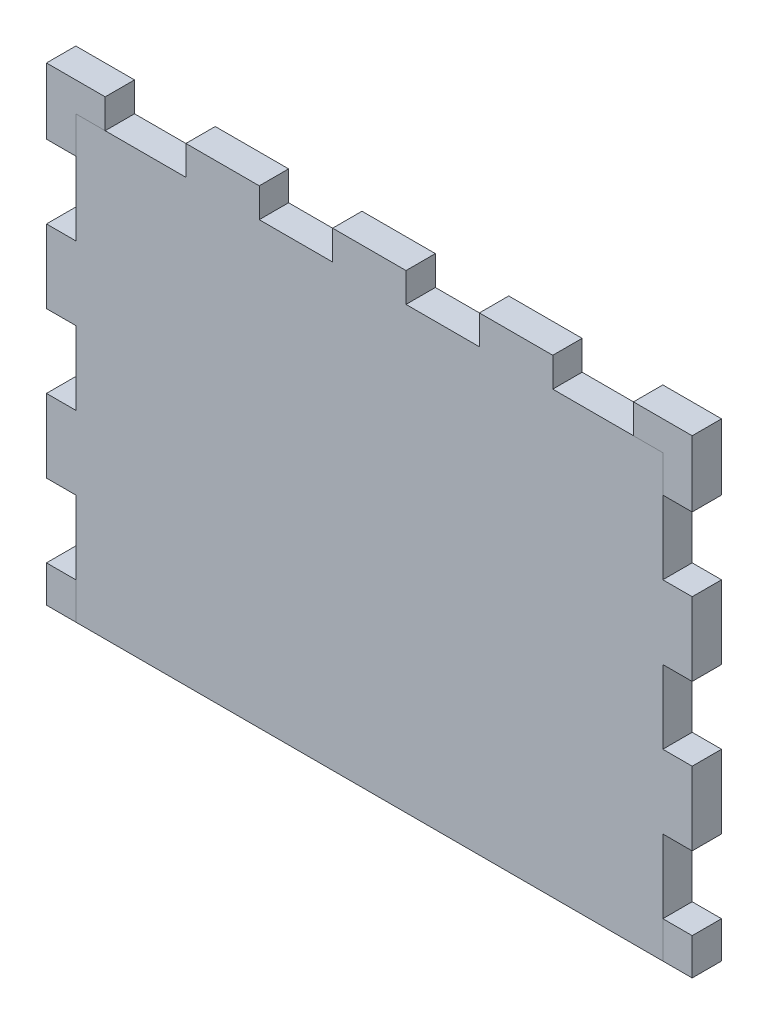
SolidWorks part; units mm, degrees
ref_plane "Front Plane" through (0, 0, 0) normal (0, 0, 1) x (1, 0, 0)
ref_plane "Top Plane" through (0, 0, 0) normal (0, 1, 0) x (1, 0, 0)
ref_plane "Right Plane" through (0, 0, 0) normal (1, 0, 0) x (0, 0, -1)
sketch "Sketch1" plane through (0, 0, 0) normal (0, 0, 1) x (1, 0, 0)
  line L0 (-40, 30) -> (-20, 30)
  line L1 (-40, -30) -> (40, -30)
  line L2 (-40, -30) -> (-40, 30)
  line L3 (-40, 30) -> (40, 30)
  line L4 (40, -30) -> (40, 30)
  line L5 (0, 30) -> (0, -30) construction
  line L6 (-40, 0) -> (40, 0) construction
  line L7 (-20, 30) -> (0, 30)
  line L8 (0, 30) -> (20, 30)
  line L9 (40, -30) -> (40, -10)
  line L10 (40, -10) -> (40, 10)
  line L11 (-40, -30) -> (-40, -10)
  line L12 (-40, -10) -> (-40, 10)
  line L13 (-40, -30) -> (-44, -30)
  line L14 (-44, 5) -> (-36, 5)
  line L15 (-44, 5) -> (-44, 15)
  line L16 (-44, 15) -> (-36, 15)
  line L17 (-36, 5) -> (-36, 15)
  line L18 (-40, 15) -> (-40, 5) construction
  line L19 (-44, 10) -> (-36, 10) construction
  line L20 (-44, -15) -> (-36, -15)
  line L21 (-44, -15) -> (-44, -5)
  line L22 (-44, -5) -> (-36, -5)
  line L23 (-36, -15) -> (-36, -5)
  line L24 (-40, -5) -> (-40, -15) construction
  line L25 (-44, -10) -> (-36, -10) construction
  line L26 (-25, 26) -> (-15, 26)
  line L27 (-25, 26) -> (-25, 34)
  line L28 (-25, 34) -> (-15, 34)
  line L29 (-15, 26) -> (-15, 34)
  line L30 (-20, 34) -> (-20, 26) construction
  line L31 (-25, 30) -> (-15, 30) construction
  line L32 (-5, 26) -> (5, 26)
  line L33 (-5, 26) -> (-5, 34)
  line L34 (-5, 34) -> (5, 34)
  line L35 (5, 26) -> (5, 34)
  line L36 (0, 34) -> (0, 26) construction
  line L37 (-5, 30) -> (5, 30) construction
  line L38 (15, 26) -> (25, 26)
  line L39 (15, 26) -> (15, 34)
  line L40 (15, 34) -> (25, 34)
  line L41 (25, 26) -> (25, 34)
  line L42 (20, 34) -> (20, 26) construction
  line L43 (15, 30) -> (25, 30) construction
  line L44 (36, 5) -> (44, 5)
  line L45 (36, 5) -> (36, 15)
  line L46 (36, 15) -> (44, 15)
  line L47 (44, 5) -> (44, 15)
  line L48 (40, 15) -> (40, 5) construction
  line L49 (36, 10) -> (44, 10) construction
  line L50 (36, -15) -> (44, -15)
  line L51 (36, -15) -> (36, -5)
  line L52 (36, -5) -> (44, -5)
  line L53 (44, -15) -> (44, -5)
  line L54 (40, -5) -> (40, -15) construction
  line L55 (36, -10) -> (44, -10) construction
  line L56 (-44, 25) -> (-36, 25)
  line L57 (-44, 25) -> (-44, 35)
  line L58 (-44, 35) -> (-36, 35)
  line L59 (-36, 25) -> (-36, 35)
  line L60 (-40, 35) -> (-40, 25) construction
  line L61 (-44, 30) -> (-36, 30) construction
  line L62 (36, 25) -> (44, 25)
  line L63 (36, 25) -> (36, 35)
  line L64 (36, 35) -> (44, 35)
  line L65 (44, 25) -> (44, 35)
  line L66 (40, 35) -> (40, 25) construction
  line L67 (36, 30) -> (44, 30) construction
  line L68 (36, -35) -> (44, -35)
  line L69 (36, -35) -> (36, -25)
  line L70 (36, -25) -> (44, -25)
  line L71 (44, -35) -> (44, -25)
  line L72 (40, -25) -> (40, -35) construction
  line L73 (36, -30) -> (44, -30) construction
  line L74 (-44, -35) -> (-36, -35)
  line L75 (-44, -35) -> (-44, -25)
  line L76 (-44, -25) -> (-36, -25)
  line L77 (-36, -35) -> (-36, -25)
  line L78 (-40, -25) -> (-40, -35) construction
  line L79 (-44, -30) -> (-36, -30) construction
  line L80 (-44, -30) -> (-44, -25)
  line L81 (-40, -25) -> (-40, -30)
  point P0 (0, 0)
  dimension "D1" = 80
  dimension "D2" = 60
  dimension "D3" = 20
  dimension "D4" = 20
  dimension "D5" = 20
  dimension "D6" = 20
  dimension "D7" = 20
  dimension "D8" = 20
  dimension "D9" = 20
  dimension "D10" = 8
  dimension "D11" = 8
  dimension "D12" = 8
  dimension "D13" = 8
  dimension "D14" = 8
  dimension "D15" = 8
  dimension "D16" = 8
  dimension "D17" = 8
  dimension "D18" = 8
  dimension "D19" = 8
  dimension "D20" = 8
  dimension "D21" = 10
  dimension "D22" = 10
  dimension "D23" = 10
  dimension "D24" = 10
  dimension "D25" = 10
  dimension "D26" = 10
  dimension "D27" = 10
  dimension "D28" = 10
  dimension "D29" = 10
  dimension "D30" = 10
  dimension "D31" = 10
extrude "Boss-Extrude1" add sketch "Sketch1" along normal blind 4 contours L77 L1 L69 L70 L9 L50 L51 L52 L10 L44 L45 L46 L4 L62 L63 L3 L41 L38 L39 L8 L35 L32 L33 L7 L29 L26 L27 L59 L56 L2 L16 L17 L14 L12 L22 L23 L20 L11 L76 | L14 L17 L16 L2 L12 | L16 L15 L14 L12 L2 | L20 L23 L22 L2 L11 | L22 L21 L20 L11 L2 | L1 L77 L76 L2 | L70 L69 L1 L4 | L52 L51 L50 L9 L4 | L50 L53 L52 L4 L9 | L46 L45 L44 L10 L4 | L44 L47 L46 L4 L10 | L63 L62 L4 L3 | L38 L41 L3 L39 | L3 L41 L40 L39 | L32 L35 L3 L33 | L3 L35 L34 L33 | L56 L59 L0 L2 | L26 L29 L3 L27 | L3 L29 L28 L27
sketch "Sketch2" plane through (0, 0, 4) normal (0, 0, 1) x (1, 0, 0)
  line L0 (-36, -30) -> (-44, -30)
  line L1 (-44, 25) -> (-36, 25)
  line L2 (-44, 25) -> (-44, 35)
  line L3 (-44, 35) -> (-36, 35)
  line L4 (-36, 25) -> (-36, 35)
  line L5 (-40, 35) -> (-40, 25) construction
  line L6 (-44, 30) -> (-36, 30) construction
  line L7 (36, 25) -> (44, 25)
  line L8 (36, 25) -> (36, 35)
  line L9 (36, 35) -> (44, 35)
  line L10 (44, 25) -> (44, 35)
  line L11 (40, 35) -> (40, 25) construction
  line L12 (36, 30) -> (44, 30) construction
  line L13 (36, -35) -> (44, -35)
  line L14 (36, -35) -> (36, -25)
  line L15 (36, -25) -> (44, -25)
  line L16 (44, -35) -> (44, -25)
  line L17 (40, -25) -> (40, -35) construction
  line L18 (36, -30) -> (44, -30) construction
  line L19 (-44, -35) -> (-36, -35)
  line L20 (-44, -35) -> (-44, -25)
  line L21 (-44, -25) -> (-36, -25)
  line L22 (-36, -35) -> (-36, -25)
  line L23 (-40, -25) -> (-40, -35) construction
  line L24 (-44, -30) -> (-36, -30) construction
  line L25 (36, -30) -> (44, -30)
  line L26 (-36, 30) -> (-36, 34)
  line L27 (-36, 34) -> (-44, 34)
  line L28 (36, 30) -> (36, 34)
  line L29 (36, 34) -> (44, 34)
  point P0 (-40, 30)
  point P4 (40, 30)
  point P8 (40, -30)
  point P12 (-40, -30)
  line M8 (40, -30) -> (40, -15)
  line M16 (40, 15) -> (40, 30)
  line M17 (40, 30) -> (25, 30)
  line M29 (-25, 30) -> (-40, 30)
  line M30 (-40, 30) -> (-40, 15)
  line M38 (-40, -15) -> (-40, -30)
  dimension "D1" = 8
  dimension "D2" = 10
  dimension "D3" = 8
  dimension "D4" = 10
  dimension "D5" = 8
  dimension "D6" = 10
  dimension "D7" = 8
  dimension "D8" = 10
  dimension "D9" = 4
  dimension "D10" = 4
extrude "Boss-Extrude2" add sketch "Sketch2" against normal blind 4 separate body contours L4 L27 L2 L1 M30 M29 | L29 L8 L7 L10 M17 M16 | L25 L16 L15 M8 | L21 L20 L0 M38
